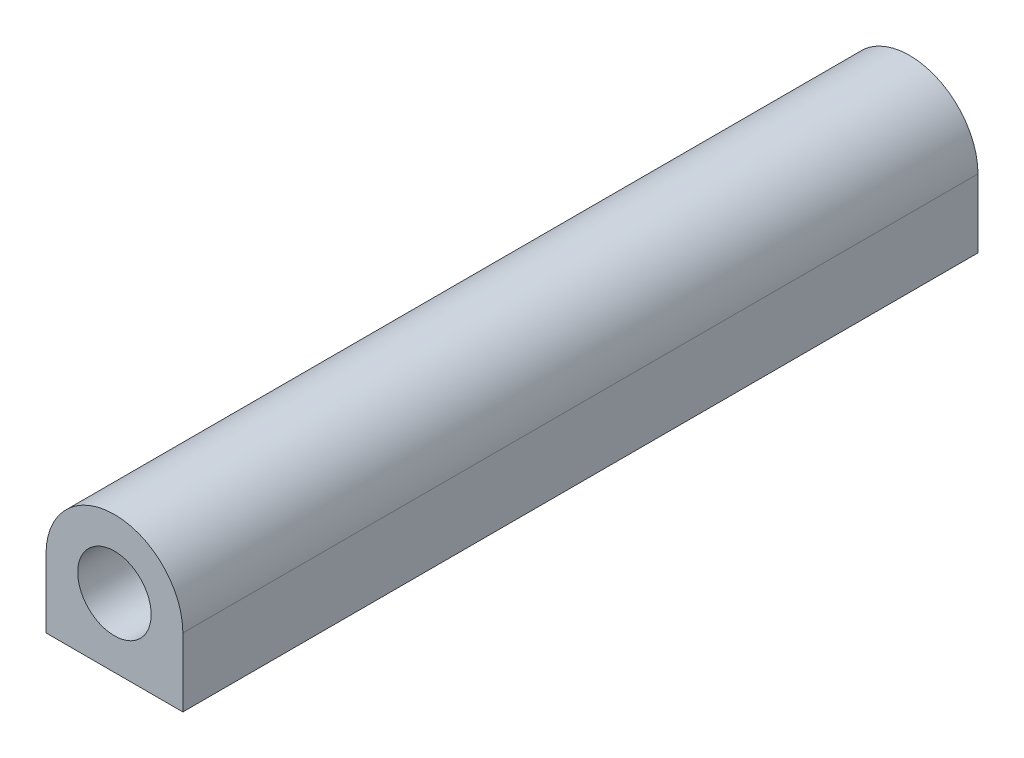
SolidWorks part; units mm, degrees
ref_plane "Front Plane" through (0, 0, 0) normal (0, 0, 1) x (1, 0, 0)
ref_plane "Top Plane" through (0, 0, 0) normal (0, 1, 0) x (1, 0, 0)
ref_plane "Right Plane" through (0, 0, 0) normal (1, 0, 0) x (0, 0, -1)
sketch "Sketch1" plane through (0, 0, 0) normal (0, 0, 1) x (1, 0, 0)
  circle A0 centre (0, 0) radius 1.475
  circle A1 centre (0, 0) radius 2.75
  dimension "D1" = 2.95
  dimension "D2" = 5.5
extrude "Boss-Extrude1" add sketch "Sketch1" along normal blind 31.95
sketch "Sketch2" plane through (0, 0, 31.95) normal (0, 0, 1) x (1, 0, 0)
  line L1 (-2.75, 0) -> (2.75, 0)
  line L2 (-2.75, 0) -> (-2.75, -2.75)
  line L3 (-2.75, -2.75) -> (2.75, -2.75)
  line L4 (2.75, 0) -> (2.75, -2.75)
  circle A0 centre (0, 0) radius 2.75
  circle M1 centre (0, 0) radius 2.75
extrude "Boss-Extrude2" add sketch "Sketch2" against normal up to surface (31.95 mm away) contours L2 L3 M1 | L4 L3 M1 up to face at (2.75, 0, 0)
sketch "Sketch3" plane through (0, 0, 0) normal (0, 0, -1) x (-1, 0, 0)
  circle A0 centre (0, 0) radius 1.475
extrude "Boss-Extrude3" add sketch "Sketch3" against normal up to surface (31.95 mm away) up to face at (0, -0.6875, 31.95)
sketch "Sketch4" plane through (0, 0, 0) normal (0, 0, -1) x (-1, 0, 0)
  circle A0 centre (0, 0) radius 1.475
  dimension "D1" = 2.95
extrude "Cut-Extrude1" cut sketch "Sketch4" against normal blind 10
sketch "Sketch5" plane through (0, 0, 31.95) normal (0, 0, 1) x (1, 0, 0)
  circle A0 centre (0, 0) radius 1.475
  dimension "D1" = 2.95
extrude "Cut-Extrude2" cut sketch "Sketch5" against normal blind 10
